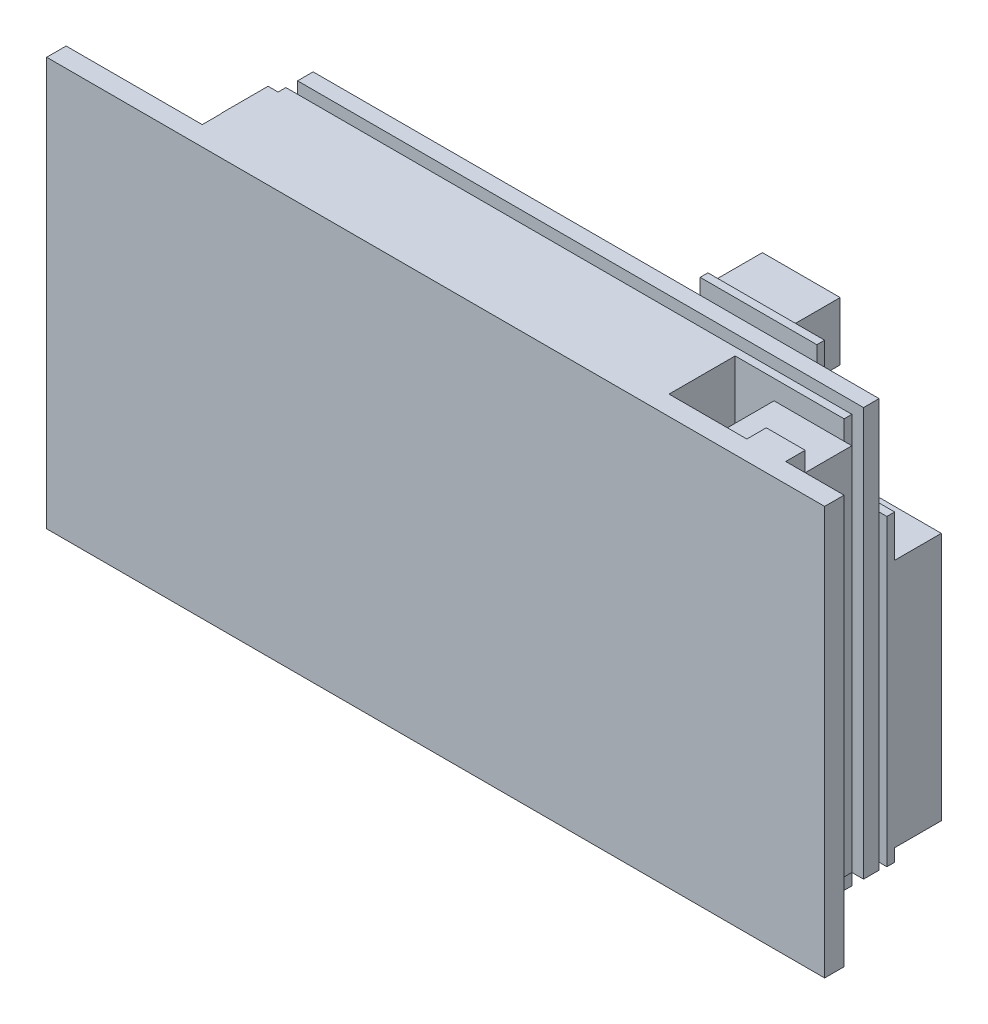
SolidWorks part; units mm, degrees
ref_plane "Front Plane" through (0, 0, 0) normal (0, 0, 1) x (1, 0, 0)
ref_plane "Top Plane" through (0, 0, 0) normal (0, 1, 0) x (1, 0, 0)
ref_plane "Right Plane" through (0, 0, 0) normal (1, 0, 0) x (0, 0, -1)
ref_plane "Plane1" through (0, 0, 0) normal (0, 0, 1) x (1, 0, 0)
ref_plane "Plane2" through (0, 0, 0) normal (0, 1, 0) x (1, 0, 0)
ref_plane "Plane3" through (0, 0, 0) normal (1, 0, 0) x (0, 0, -1)
sketch "Sketch2" plane through (0, 0, 0) normal (0, 0, 1) x (1, 0, 0)
  line L1 (0, 0) -> (200, 0)
  line L2 (0, 0) -> (0, 105)
  line L3 (0, 105) -> (200, 105)
  line L4 (200, 0) -> (200, 105)
  dimension "D1" = 105
  dimension "D2" = 200
extrude "Boss-Extrude1" add sketch "Sketch2" along normal blind 5
sketch "Sketch3" plane through (0, 0, 0) normal (0, 0, -1) x (-1, 0, 0)
  line L0 (-200, 105) -> (0, 105) construction
  line L1 (-185, 105) -> (-175, 105)
  line L2 (-185, 105) -> (-185, 0)
  line L3 (-185, 0) -> (-175, 0)
  line L4 (-175, 105) -> (-175, 0)
  line L5 (2.75, 0) -> (-2.75, 0) construction
  line L6 (-200, 0) -> (-200, 105) construction
  dimension "D1" = 15
  dimension "D2" = 10
extrude "Boss-Extrude2" add sketch "Sketch3" along normal blind 5
sketch "Sketch4" plane through (0, 0, 0) normal (0, 0, 1) x (1, 0, 0)
  line L0 (5.5, 0) -> (-5.5, 0) construction
  line L1 (155, 0) -> (35, 0)
  line L2 (155, 0) -> (155, 10)
  line L3 (155, 10) -> (35, 10)
  line L4 (35, 0) -> (35, 10)
  line L5 (0, -5.5) -> (0, 5.5) construction
  line L6 (175, 0) -> (175, 105) construction
  line L7 (0, 52.5) -> (208.8547, 52.5) construction
  line L8 (35, 105) -> (35, 95)
  line L9 (155, 105) -> (35, 105)
  line L10 (155, 105) -> (155, 95)
  line L11 (155, 95) -> (35, 95)
  dimension "D1" = 35
  dimension "D2" = 20
  dimension "D3" = 10
  dimension "D4" = 52.5
extrude "Boss-Extrude3" add sketch "Sketch4" against normal blind 5
sketch "Sketch5" plane through (0, 0, 0) normal (0, 0, 1) x (1, 0, 0)
  line L0 (0, -5.5) -> (0, 5.5) construction
  line L1 (3, 30) -> (38, 30)
  line L2 (3, 30) -> (3, 80)
  line L3 (3, 80) -> (38, 80)
  line L4 (38, 30) -> (38, 80)
  line L5 (5.5, 0) -> (-5.5, 0) construction
  dimension "D1" = 3
  dimension "D2" = 30
  dimension "D3" = 50
  dimension "D4" = 35
extrude "Boss-Extrude4" add sketch "Sketch5" against normal blind 5
ref_plane "Plane4" through (0, 0, -5) normal (0, 0, 1) x (1, 0, 0)
sketch "Sketch7" plane through (0, 0, -5) normal (0, 0, 1) x (1, 0, 0)
  line L0 (185, 105) -> (185, 0) construction
  line L1 (185, 100) -> (165, 100)
  line L2 (185, 100) -> (185, 5)
  line L3 (185, 5) -> (165, 5)
  line L4 (165, 100) -> (165, 5)
  line L5 (175, 105) -> (155, 105) construction
  line L6 (5.5, 0) -> (-5.5, 0) construction
  line L7 (155, 0) -> (155, 10) construction
  line L8 (155, 0) -> (39.5022, 0)
  line L9 (155, 0) -> (155, 20)
  line L10 (155, 20) -> (39.5022, 20)
  line L11 (39.5022, 0) -> (39.5022, 20)
  line L13 (155, 105) -> (34.919, 105)
  line L14 (155, 105) -> (155, 85)
  line L15 (155, 85) -> (34.919, 85)
  line L16 (34.919, 105) -> (34.919, 85)
  line L17 (31.94, 66.5932) -> (46.1478, 66.5932)
  line L18 (31.94, 66.5932) -> (31.94, 73.5932)
  line L19 (31.94, 73.5932) -> (46.1478, 73.5932)
  line L20 (46.1478, 66.5932) -> (46.1478, 73.5932)
  line L21 (31.94, 41.8441) -> (46.1478, 41.8441)
  line L22 (31.94, 41.8441) -> (31.94, 51.8441)
  line L23 (31.94, 51.8441) -> (46.1478, 51.8441)
  line L24 (46.1478, 41.8441) -> (46.1478, 51.8441)
  dimension "D1" = 5
  dimension "D2" = 5
  dimension "D3" = 20
  dimension "D4" = 20
  dimension "D5" = 20
  dimension "D6" = 7
  dimension "D7" = 10
extrude "Boss-Extrude5" add sketch "Sketch7" against normal blind 12
ref_plane "Plane5" through (0, 0, -17) normal (0, 0, 1) x (1, 0, 0)
sketch "Sketch8" plane through (0, 0, -17) normal (0, 0, 1) x (1, 0, 0)
  line L0 (12.1, 0) -> (-12.1, 0) construction
  line L1 (183, 0) -> (37.5, 0)
  line L2 (183, 0) -> (183, 105)
  line L3 (183, 105) -> (37.5, 105)
  line L4 (37.5, 0) -> (37.5, 105)
  line L5 (35, 105) -> (0, 105) construction
  line L6 (185, 5) -> (185, 100) construction
  dimension "D1" = 145.5
  dimension "D2" = 2
extrude "Boss-Extrude6" add sketch "Sketch8" against normal blind 2
ref_plane "Plane6" through (0, 0, -22) normal (0, 0, 1) x (1, 0, 0)
sketch "Sketch9" plane through (0, 0, -22) normal (0, 0, 1) x (1, 0, 0)
  line L0 (37.5, 0) -> (183, 0)
  line L1 (37.5, 105) -> (37.5, 0) construction
  line L2 (13.2, 0) -> (-13.2, 0) construction
  line L3 (183, 0) -> (183, 105)
  line L4 (183, 105) -> (37.5, 105)
  line L5 (37.5, 105) -> (37.5, 77)
  line L6 (37.5, 77) -> (107.5, 77)
  line L7 (107.5, 77) -> (107.5, 28)
  line L8 (107.5, 28) -> (37.5, 28)
  line L9 (37.5, 28) -> (37.5, 0)
  dimension "D1" = 28
  dimension "D2" = 28
  dimension "D3" = 70
extrude "Boss-Extrude7" add sketch "Sketch9" against normal blind 4 separate body
sketch "Sketch10" plane through (0, 0, -17) normal (0, 0, 1) x (1, 0, 0)
  line L0 (107.5, 28) -> (37.5, 28) construction
  line L1 (52.5, 28) -> (103.5, 28)
  line L2 (52.5, 28) -> (52.5, 77)
  line L3 (52.5, 77) -> (103.5, 77)
  line L4 (103.5, 28) -> (103.5, 77)
  line L5 (37.5, 77) -> (107.5, 77) construction
  line L6 (37.5, 105) -> (37.5, 0) construction
  line L7 (107.5, 77) -> (107.5, 28) construction
  dimension "D1" = 15
  dimension "D2" = 4
extrude "Boss-Extrude8" add sketch "Sketch10" against normal blind 14
ref_plane "Plane7" through (0, 0, -28) normal (0, 0, 1) x (1, 0, 0)
sketch "Sketch11" plane through (0, 0, -28) normal (0, 0, 1) x (1, 0, 0)
  line L1 (183, -0.2385) -> (128, -0.2385)
  line L2 (183, -0.2385) -> (183, 77.7615)
  line L3 (183, 77.7615) -> (128, 77.7615)
  line L4 (128, -0.2385) -> (128, 77.7615)
  line L6 (183, 5) -> (183, 100) construction
  dimension "D1" = 78
  dimension "D2" = 55
  dimension "D3" = 0
extrude "Boss-Extrude9" add sketch "Sketch11" against normal blind 2 separate body
ref_plane "Plane8" through (0, 0, -30) normal (0, 0, 1) x (1, 0, 0)
sketch "Sketch12" plane through (0, 0, -30) normal (0, 0, 1) x (1, 0, 0)
  line L0 (183, -0.2385) -> (183, 77.7615) construction
  line L1 (183, 67) -> (163, 67)
  line L2 (183, 67) -> (183, 3)
  line L3 (183, 3) -> (163, 3)
  line L4 (163, 67) -> (163, 3)
  line L5 (19.8, 0) -> (-19.8, 0) construction
  line L7 (158, 0) -> (143, 0)
  line L8 (158, 0) -> (158, 20)
  line L9 (158, 20) -> (143, 20)
  line L10 (143, 0) -> (143, 20)
  dimension "D1" = 64
  dimension "D2" = 3
  dimension "D5" = 15
  dimension "D6" = 20
extrude "Boss-Extrude10" add sketch "Sketch12" against normal blind 12
ref_plane "Plane9" through (0, 0, -32) normal (0, 0, 1) x (1, 0, 0)
sketch "Sketch13" plane through (0, 0, -32) normal (0, 0, 1) x (1, 0, 0)
  line L0 (183, 105) -> (37.5, 105) construction
  line L1 (163, 105) -> (133, 105)
  line L2 (163, 105) -> (163, 85)
  line L3 (163, 85) -> (133, 85)
  line L4 (133, 105) -> (133, 85)
  line L5 (183, 0) -> (183, 105) construction
  dimension "D1" = 30
  dimension "D2" = 20
  dimension "D3" = 20
extrude "Boss-Extrude11" add sketch "Sketch13" along normal blind 2 separate body
ref_plane "Plane11" through (0, 0, -34) normal (0, 0, 1) x (1, 0, 0)
sketch "Sketch14" plane through (0, 0, -34) normal (0, 0, 1) x (1, 0, 0)
  line L0 (133, 105) -> (133, 85) construction
  line L1 (133, 102.5) -> (153, 102.5)
  line L2 (133, 102.5) -> (133, 87.5)
  line L3 (133, 87.5) -> (153, 87.5)
  line L4 (153, 102.5) -> (153, 87.5)
  line L5 (133, 85) -> (163, 85) construction
  dimension "D1" = 15
  dimension "D2" = 2.5
  dimension "D3" = 20
extrude "Boss-Extrude12" add sketch "Sketch14" against normal blind 12
